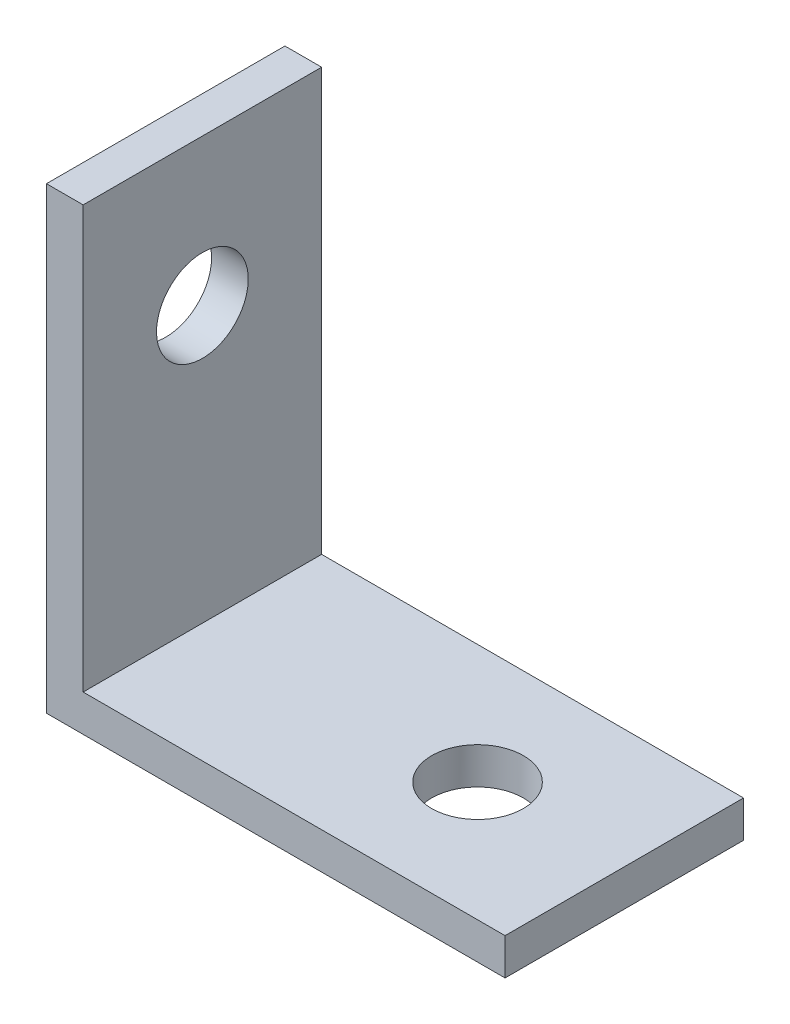
SolidWorks part; units mm, degrees
ref_plane "Plano frontal" through (0, 0, 0) normal (0, 0, 1) x (1, 0, 0)
ref_plane "Plano superior" through (0, 0, 0) normal (0, 1, 0) x (1, 0, 0)
ref_plane "Plano direito" through (0, 0, 0) normal (1, 0, 0) x (0, 0, -1)
sketch "Esboço1" plane through (0, 0, 0) normal (0, 0, 1) x (1, 0, 0)
  line L0 (3.5107, 8.612) -> (3.5107, 6.612)
  line L1 (3.5107, 6.612) -> (-21.4893, 6.612)
  line L2 (-21.4893, 6.612) -> (-21.4893, 31.612)
  line L3 (-21.4893, 31.612) -> (-19.4893, 31.612)
  line L4 (-19.4893, 31.612) -> (-19.4893, 8.612)
  line L5 (-19.4893, 8.612) -> (3.5107, 8.612)
  dimension "D1" = 25
  dimension "D2" = 2
extrude "Ressalto-extrusão1" add sketch "Esboço1" along normal blind 13
sketch "Esboço3" plane through (-19.4893, 0, 0) normal (1, 0, 0) x (0, 0, -1)
  line L1 (-13, 31.612) -> (0, 31.612) construction
  line L3 (0, 8.612) -> (0, 31.612) construction
  circle A0 centre (-6.5, 23.612) radius 2.5
  point P5 (0, 20.112)
  dimension "D2" = 5
  dimension "D1" = 8
  dimension "D3" = 6.5
extrude "Corte-extrusão1" cut sketch "Esboço3" against normal blind 8 contours A0
sketch "Esboço4" plane through (0, 8.612, 0) normal (0, 1, 0) x (1, 0, 0)
  line L1 (3.5107, -13) -> (-19.4893, -13) construction
  line L2 (3.5107, -13) -> (3.5107, 0) construction
  circle A0 centre (-4.4893, -6.5) radius 2.5
  dimension "D1" = 5
  dimension "D2" = 8
  dimension "D3" = 6.5
extrude "Corte-extrusão2" cut sketch "Esboço4" against normal blind 8
